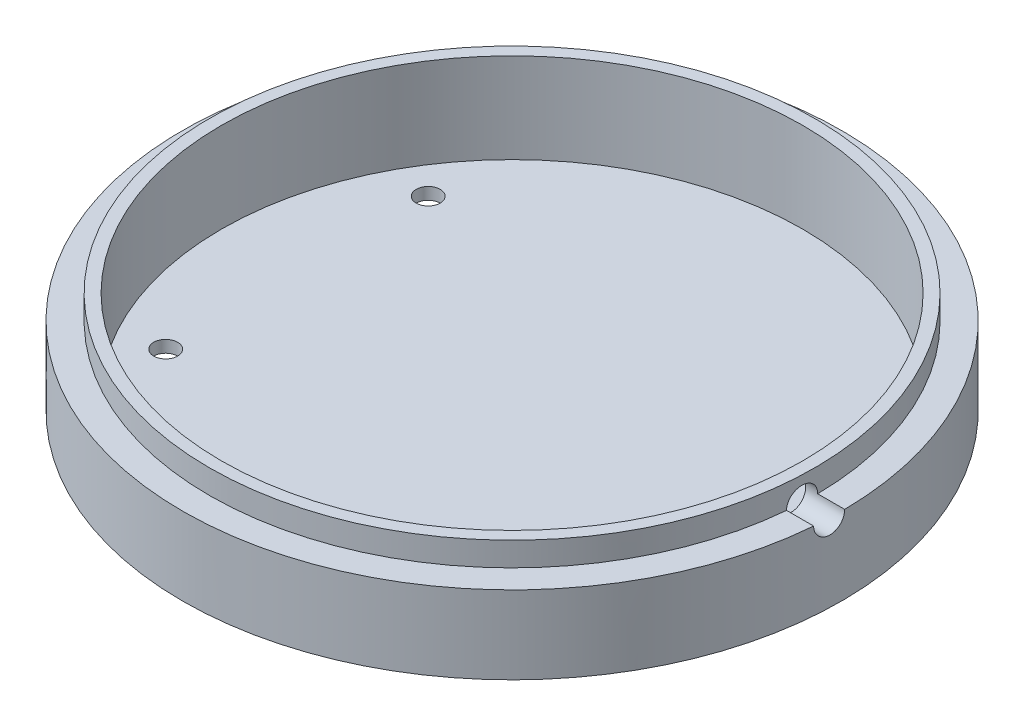
SolidWorks part; units mm, degrees
ref_plane "Front Plane" through (0, 0, 0) normal (0, 0, 1) x (1, 0, 0)
ref_plane "Top Plane" through (0, 0, 0) normal (0, 1, 0) x (1, 0, 0)
ref_plane "Right Plane" through (0, 0, 0) normal (1, 0, 0) x (0, 0, -1)
sketch "Sketch2" plane through (0, 0, 0) normal (0, 1, 0) x (1, 0, 0)
  circle A0 centre (0, 0) radius 55
  circle A1 centre (0, 0) radius 52.5
  dimension "D1" = 110
  dimension "D2" = 105
extrude "Boss-Extrude2" add sketch "Sketch2" along normal blind 13 contours A0
sketch "Sketch3" plane through (0, 0, 0) normal (0, -1, 0) x (1, 0, 0)
  circle A0 centre (0, 0) radius 52.5
  dimension "D1" = 105
sketch "Sketch7" plane through (0, 13, 0) normal (0, 1, 0) x (1, 0, 0)
  circle A0 centre (0, 0) radius 50.5
  dimension "D1" = 101
extrude "Boss-Extrude3" add sketch "Sketch7" along normal blind 4
sketch "Sketch8" plane through (0, 17, 0) normal (0, 1, 0) x (1, 0, 0)
  circle A0 centre (0, 0) radius 48.5
  dimension "D1" = 97
extrude "Cut-Extrude3" cut sketch "Sketch8" against normal blind 15
sketch "Sketch9" plane through (0, 2, 0) normal (0, 1, 0) x (1, 0, 0)
  line L1 (-38, -24) -> (38, -24)
  line L2 (-38, -24) -> (-38, 24)
  line L3 (-38, 24) -> (38, 24)
  line L4 (38, -24) -> (38, 24)
  line L5 (36, -2.1049) -> (39.1627, -2.1049)
  line L6 (36, -2.1049) -> (36, 0.5)
  line L7 (36, 0.5) -> (39.1627, 0.5)
  line L8 (39.1627, -2.1049) -> (39.1627, 0.5)
  circle A0 centre (-35.8, -22) radius 2
  circle A1 centre (36, -22) radius 2
  circle A2 centre (36, 22) radius 2
  circle A3 centre (-36, 22) radius 2
  dimension "D5" = 4
  dimension "D6" = 4
  dimension "D7" = 4
  dimension "D8" = 4
  dimension "D1" = 76
  dimension "D2" = 38
  dimension "D3" = 48
  dimension "D4" = 24
  dimension "D9" = 2.2
  dimension "D10" = 2
  dimension "D11" = 2
  dimension "D12" = 2
  dimension "D13" = 2
  dimension "D14" = 2
  dimension "D15" = 21.5
extrude "Cut-Extrude4" cut sketch "Sketch9" against normal blind 15 contours A1 | A3 | A0 | A2 | L6 L5 L8 L7
sketch "Sketch10" plane through (36, 0, 0) normal (1, 0, 0) x (0, 0, -1)
  line L2 (0.5, 0) -> (0.5, 2) construction
  line L5 (55, 13) -> (-55, 13) construction
  circle A2 centre (-2, 13) radius 2.5
  point P6 (-17.9485, 15.2797)
  point P11 (-2.0048, 1.4535)
  dimension "D1" = 5
  dimension "D2" = 2.5
  dimension "D3" = 0
extrude "Cut-Extrude5" cut sketch "Sketch10" against normal blind 1 and the other way blind 20
sketch "Sketch11" plane through (0, 2, 0) normal (0, 1, 0) x (1, 0, 0)
  line L1 (40.3308, -4.078) -> (34.0566, -4.078)
  line L2 (40.3308, -4.078) -> (40.3308, 3.3016)
  line L3 (40.3308, 3.3016) -> (34.0566, 3.3016)
  line L4 (34.0566, -4.078) -> (34.0566, 3.3016)
sketch "Sketch12" plane through (0, 0, 0) normal (0, -1, 0) x (-1, 0, 0)
  line L1 (-32.0049, 3.5231) -> (-42.9913, 3.5231)
  line L2 (-32.0049, 3.5231) -> (-32.0049, -4.6945)
  line L3 (-32.0049, -4.6945) -> (-42.9913, -4.6945)
  line L4 (-42.9913, 3.5231) -> (-42.9913, -4.6945)
extrude "Boss-Extrude5" add sketch "Sketch11" along normal blind 0.01 and the other way blind 2
sketch3d "3DSketch1" plane through (0, 0, 0) normal (0, 0, 1) x (1, 0, 0)
sketch3d "3DSketch2" plane through (0, 0, 0) normal (0, 0, 1) x (1, 0, 0)
  dimension "D1" = 10
